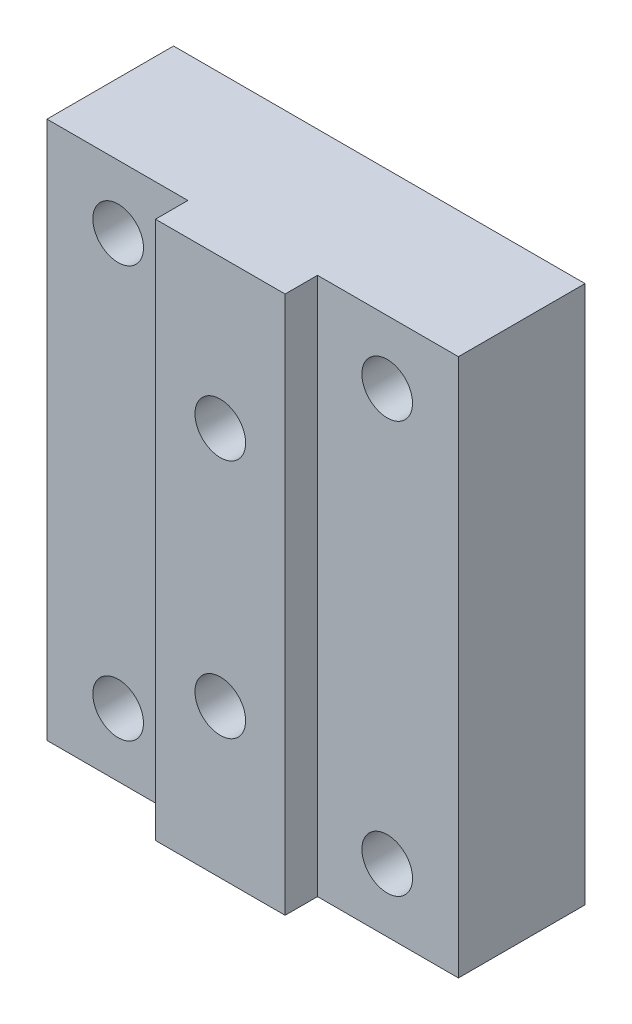
SolidWorks part; units mm, degrees
ref_plane "Front Plane" through (0, 0, 0) normal (0, 0, 1) x (1, 0, 0)
ref_plane "Top Plane" through (0, 0, 0) normal (0, 1, 0) x (1, 0, 0)
ref_plane "Right Plane" through (0, 0, 0) normal (1, 0, 0) x (0, 0, -1)
ref_plane "Plane1" through (0, 0, 508) normal (0, 0, 1) x (1, 0, 0)
sketch "Sketch1" plane through (0, 0, 508) normal (0, 0, 1) x (1, 0, 0)
  line L0 (0, 0) -> (1651, 0)
  line L1 (1651, 0) -> (1651, 2159)
  line L2 (1651, 2159) -> (0, 2159)
  line L3 (0, 2159) -> (0, 0)
  circle A0 centre (285.75, 254) radius 101.6
  circle A1 centre (1365.25, 1905) radius 101.6
  circle A2 centre (825.5, 1562.1) radius 101.6
  circle A3 centre (285.75, 1905) radius 101.6
  circle A4 centre (1365.25, 254) radius 101.6
  circle A5 centre (825.5, 596.9) radius 101.6
extrude "Boss-Extrude1" add sketch "Sketch1" against normal blind 508
sketch "Sketch2" plane through (0, 0, 508) normal (0, 0, 1) x (1, 0, 0)
  line L0 (825.5, 2159) -> (825.5, 0) construction
  line L1 (1651, 2159) -> (0, 2159) construction
  line L2 (0, 0) -> (1651, 0) construction
  line L4 (1085.5, 0) -> (565.5, 0)
  line L5 (1085.5, 0) -> (1085.5, 2159)
  line L6 (1085.5, 2159) -> (565.5, 2159)
  line L7 (565.5, 0) -> (565.5, 2159)
  line L8 (1085.5, 0) -> (565.5, 2159) construction
  line L9 (1085.5, 2159) -> (565.5, 0) construction
  circle A0 centre (825.5, 596.9) radius 101.6 construction
  circle A1 centre (825.5, 1562.1) radius 101.6 construction
  circle A2 centre (825.5, 596.9) radius 101.6
  circle A3 centre (825.5, 1562.1) radius 101.6
  point P6 (825.5, 1079.5)
  dimension "D1" = 520
extrude "Boss-Extrude2" add sketch "Sketch2" along normal blind 130
